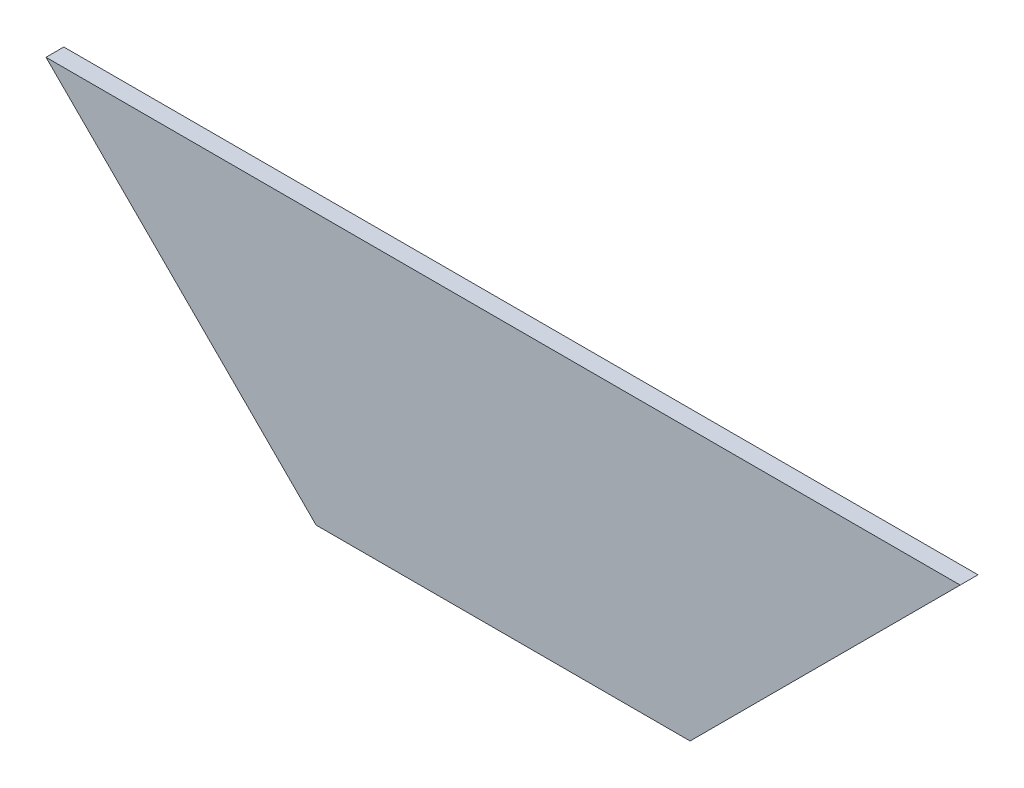
SolidWorks part; units mm, degrees
ref_plane "Plan de face" through (0, 0, 0) normal (0, 0, 1) x (1, 0, 0)
ref_plane "Plan de dessus" through (0, 0, 0) normal (0, 1, 0) x (1, 0, 0)
ref_plane "Plan de droite" through (0, 0, 0) normal (1, 0, 0) x (0, 0, -1)
sketch "Esquisse1" plane through (0, 0, 0) normal (0, 0, 1) x (1, 0, 0)
  line L0 (-63, 0) -> (63, 0)
  line L1 (63, 0) -> (154, 91)
  line L2 (154, 91) -> (-154, 91)
  line L3 (-154, 91) -> (-63, 0)
  point P3 (0, 0)
  point P6 (-46.7851, 0)
  point P7 (-27.7505, 0)
  point P8 (0, 0)
  point P9 (0, 0)
  dimension "D1" = 135
  dimension "D2" = 308
  dimension "D3" = 126
extrude "Boss.-Extru.1" add sketch "Esquisse1" along normal blind 6
